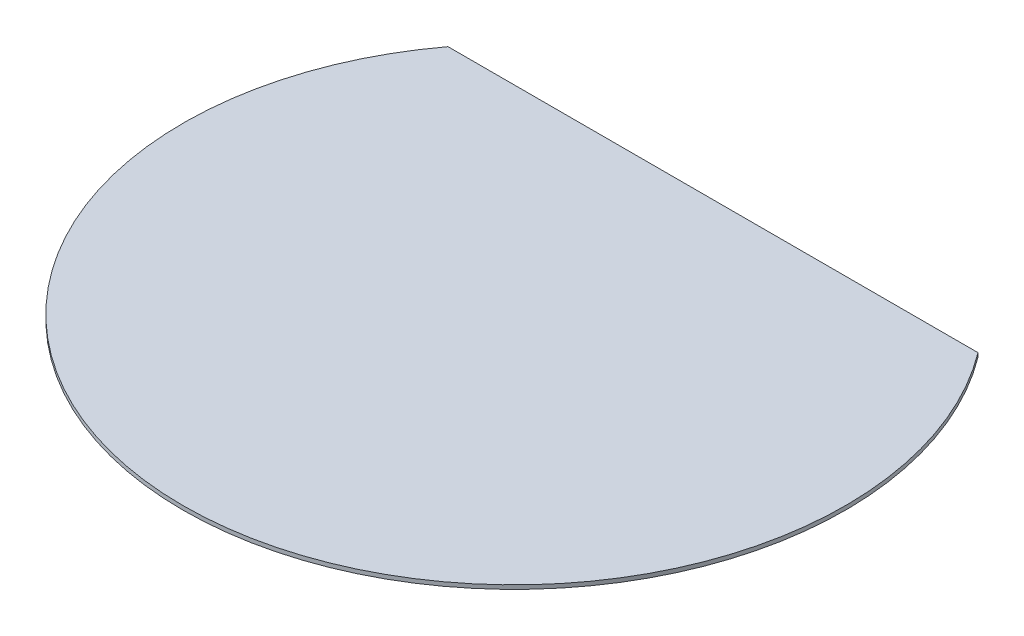
SolidWorks part; units mm, degrees
ref_plane "Front Plane" through (0, 0, 0) normal (0, 0, 1) x (1, 0, 0)
ref_plane "Top Plane" through (0, 0, 0) normal (0, 1, 0) x (1, 0, 0)
ref_plane "Right Plane" through (0, 0, 0) normal (1, 0, 0) x (0, 0, -1)
sketch "Sketch1" plane through (0, 0, 0) normal (0, 1, 0) x (1, 0, 0)
  line L0 (-848.36, 636.27) -> (848.36, 636.27)
  arc A0 (-848.36, 636.27) -> (848.36, 636.27) centre (0, 0) ccw
extrude "Boss-Extrude1" add sketch "Sketch1" along normal blind 12.7
